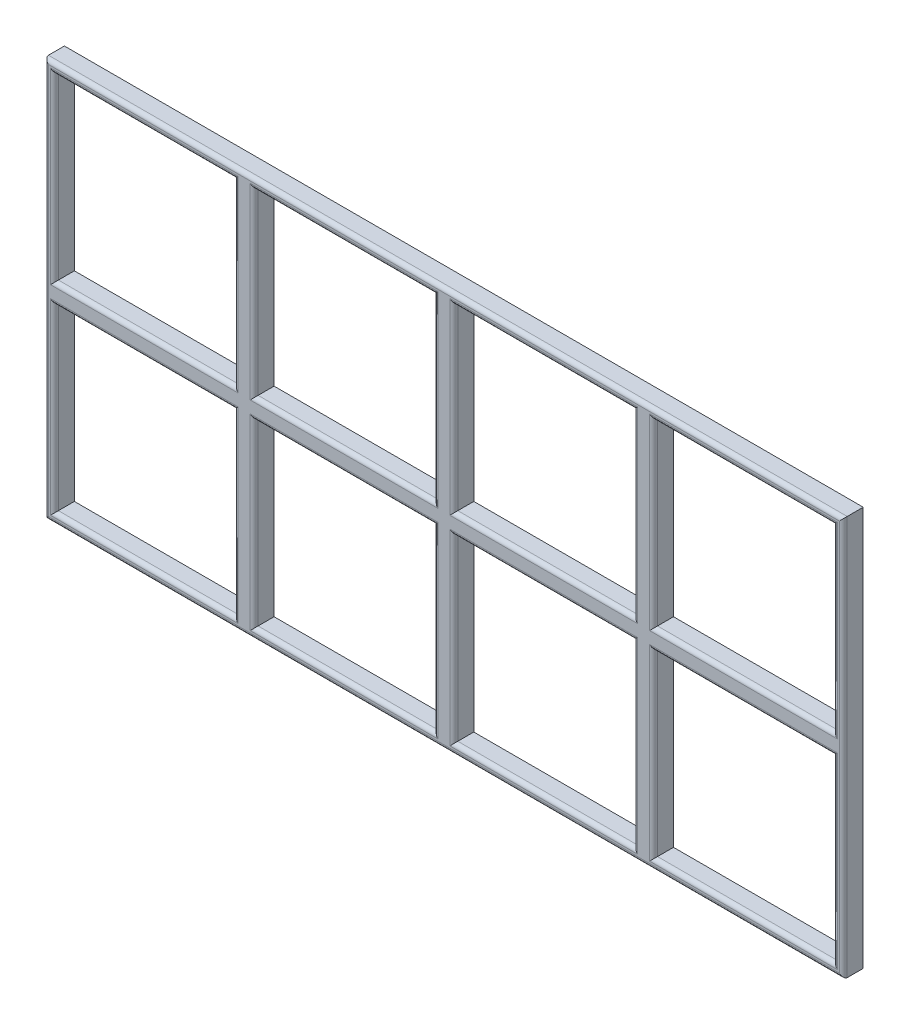
SolidWorks part; units mm, degrees
ref_plane "Front Plane" through (0, 0, 0) normal (0, 0, 1) x (1, 0, 0)
ref_plane "Top Plane" through (0, 0, 0) normal (0, 1, 0) x (1, 0, 0)
ref_plane "Right Plane" through (0, 0, 0) normal (1, 0, 0) x (0, 0, -1)
sketch "Sketch2" plane through (0, 0, 0) normal (0, 0, 1) x (1, 0, 0)
  line L2 (-100, 0) -> (-100, 100)
  line L3 (-100, 100) -> (100, 100)
  line L4 (100, 0) -> (100, 100)
  line L5 (-97.5, 52.5) -> (-52.5, 52.5)
  line L6 (-52.5, 97.5) -> (-52.5, 52.5)
  line L11 (0, 0) -> (100, 100) construction
  line L12 (-98.75, 98.75) -> (0, 0) construction
  line L18 (100, 0) -> (-100, 0)
  line L46 (-47.5, 97.5) -> (-47.5, 52.5)
  line L47 (-2.5, 97.5) -> (-2.5, 52.5)
  line L58 (-47.5, 2.5) -> (2.5, 52.5) construction
  line L59 (-47.5, 47.5) -> (-2.5, 2.5) construction
  line L64 (2.5, 2.5) -> (47.5, 47.5) construction
  line L65 (2.5, 47.5) -> (47.5, 2.5) construction
  line L69 (97.5, 2.5) -> (97.5, 47.5)
  line L70 (52.5, 2.5) -> (97.5, 47.5) construction
  line L71 (52.5, 47.5) -> (97.5, 2.5) construction
  line L74 (-47.5, 97.5) -> (-2.5, 97.5)
  line L76 (-47.5, 52.5) -> (-2.5, 97.5) construction
  line L77 (-47.5, 97.5) -> (-2.5, 52.5) construction
  line L80 (2.5, 97.5) -> (47.5, 97.5)
  line L82 (2.5, 52.5) -> (47.5, 97.5) construction
  line L83 (2.5, 97.5) -> (47.5, 52.5) construction
  line L86 (52.5, 97.5) -> (97.5, 97.5)
  line L87 (97.5, 52.5) -> (97.5, 97.5)
  line L88 (52.5, 52.5) -> (97.5, 97.5) construction
  line L89 (52.5, 97.5) -> (97.5, 52.5) construction
  line L97 (-97.5, 2.5) -> (-97.5, 47.5)
  line L100 (-97.5, 2.5) -> (-52.5, 47.5) construction
  line L101 (-97.5, 47.5) -> (-52.5, 2.5) construction
  line L103 (-97.5, 52.5) -> (-97.5, 97.5)
  line L104 (-97.5, 97.5) -> (-52.5, 97.5)
  line L106 (-97.5, 52.5) -> (-52.5, 97.5) construction
  line L107 (-97.5, 97.5) -> (-52.5, 52.5) construction
  line L108 (2.5, 97.5) -> (2.5, 52.5)
  line L109 (47.5, 97.5) -> (47.5, 52.5)
  line L158 (52.5, 97.5) -> (52.5, 52.5)
  line L159 (-97.5, 47.5) -> (-52.5, 47.5)
  line L160 (-97.5, 2.5) -> (-52.5, 2.5)
  line L177 (-47.5, 2.5) -> (-2.5, 2.5)
  line L180 (2.5, 2.5) -> (47.5, 2.5)
  line L185 (52.5, 2.5) -> (97.5, 2.5)
  line L188 (52.5, 52.5) -> (97.5, 52.5)
  line L189 (52.5, 47.5) -> (97.5, 47.5)
  line L190 (52.5, 47.5) -> (52.5, 2.5)
  line L191 (47.5, 47.5) -> (47.5, 2.5)
  line L192 (2.5, 52.5) -> (47.5, 52.5)
  line L193 (-2.5, 47.5) -> (-2.5, 2.5)
  line L194 (2.5, 47.5) -> (47.5, 47.5)
  line L195 (2.5, 47.5) -> (2.5, 2.5)
  line L196 (-52.5, 47.5) -> (-52.5, 2.5)
  line L197 (-47.5, 52.5) -> (-2.5, 52.5)
  line L198 (-47.5, 47.5) -> (-47.5, 2.5)
  line L199 (-47.5, 47.5) -> (-2.5, 47.5)
  point P0 (-75, -25)
  point P5 (75, -25)
  point P6 (75, -75)
  point P7 (25, -75)
  point P12 (-25, -75)
  point P38 (-25, -25)
  point P39 (25, 25)
  point P40 (-25, 25)
  point P41 (25, -25)
  point P58 (75, 25)
  point P63 (-25, 75)
  point P68 (25, 75)
  point P73 (75, 75)
  point P83 (-75, 25)
  point P88 (-75, 75)
  dimension "D1" = 200
extrude "Boss-Extrude1" add sketch "Sketch2" along normal blind 5
fillet "Fillet2" radius 1 36 edges at (-75, 97.5, 5) (-97.5, 75, 5) (25, 97.5, 5) (97.5, 25, 5) (-100, 50, 5) (0, 100, 5) (100, 50, 5) (-25, 97.5, 5) (75, 97.5, 5) (97.5, 75, 5) (-97.5, 25, 5) (-75, 52.5, 5) (-52.5, 75, 5) (2.5, 75, 5) (25, 52.5, 5) (47.5, 75, 5) (52.5, 25, 5) (75, 2.5, 5) (75, 47.5, 5) (-47.5, 25, 5) (-25, 2.5, 5) (-2.5, 25, 5) (-25, 47.5, 5) (2.5, 25, 5) (25, 2.5, 5) (47.5, 25, 5) (25, 47.5, 5) (-47.5, 75, 5) (-25, 52.5, 5) (-2.5, 75, 5) (52.5, 75, 5) (75, 52.5, 5) (-75, 47.5, 5) (-75, 2.5, 5) (-52.5, 25, 5) (0, 0, 5)
